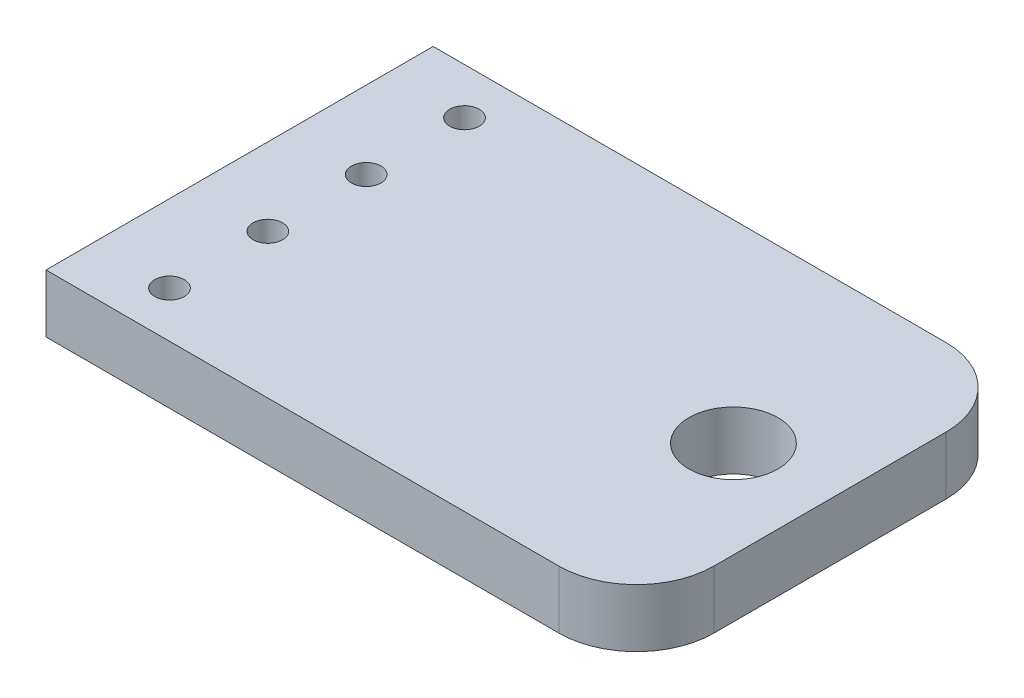
SolidWorks part; units mm, degrees
ref_plane "Front Plane" through (0, 0, 0) normal (0, 0, 1) x (1, 0, 0)
ref_plane "Top Plane" through (0, 0, 0) normal (0, 1, 0) x (1, 0, 0)
ref_plane "Right Plane" through (0, 0, 0) normal (1, 0, 0) x (0, 0, -1)
sketch "Sketch1" plane through (0, 0, 0) normal (0, 1, 0) x (1, 0, 0)
  line L0 (2, 8.81) -> (2, 1.19) construction
  line L1 (0, 0) -> (15.25, 0)
  line L2 (0, 0) -> (0, 10)
  line L3 (0, 10) -> (15.25, 10)
  line L4 (15.25, 0) -> (15.25, 10)
  circle A0 centre (12.7557, 5) radius 1.15
  circle A1 centre (2, 6.27) radius 0.381
  circle A2 centre (2, 3.73) radius 0.381
  circle A3 centre (2, 1.19) radius 0.381
  circle A4 centre (2, 8.81) radius 0.381
  point P9 (0, 5)
  point P10 (2, 5)
  point P17 (0, 0)
  point P18 (0, 0)
  dimension "D3" = 2.3
  dimension "D5" = 2.54
  dimension "D7" = 0.762
  dimension "D8" = 0.762
  dimension "D1" = 10
  dimension "D2" = 15.25
  dimension "D4" = 2
  dimension "D6" = 2.54
  dimension "D9" = 2.54
extrude "Boss-Extrude1" add sketch "Sketch1" along normal blind 1.5
fillet "Fillet2" radius 2 2 edges at (15.25, 0.75, -10) (15.25, 0.75, 0)
